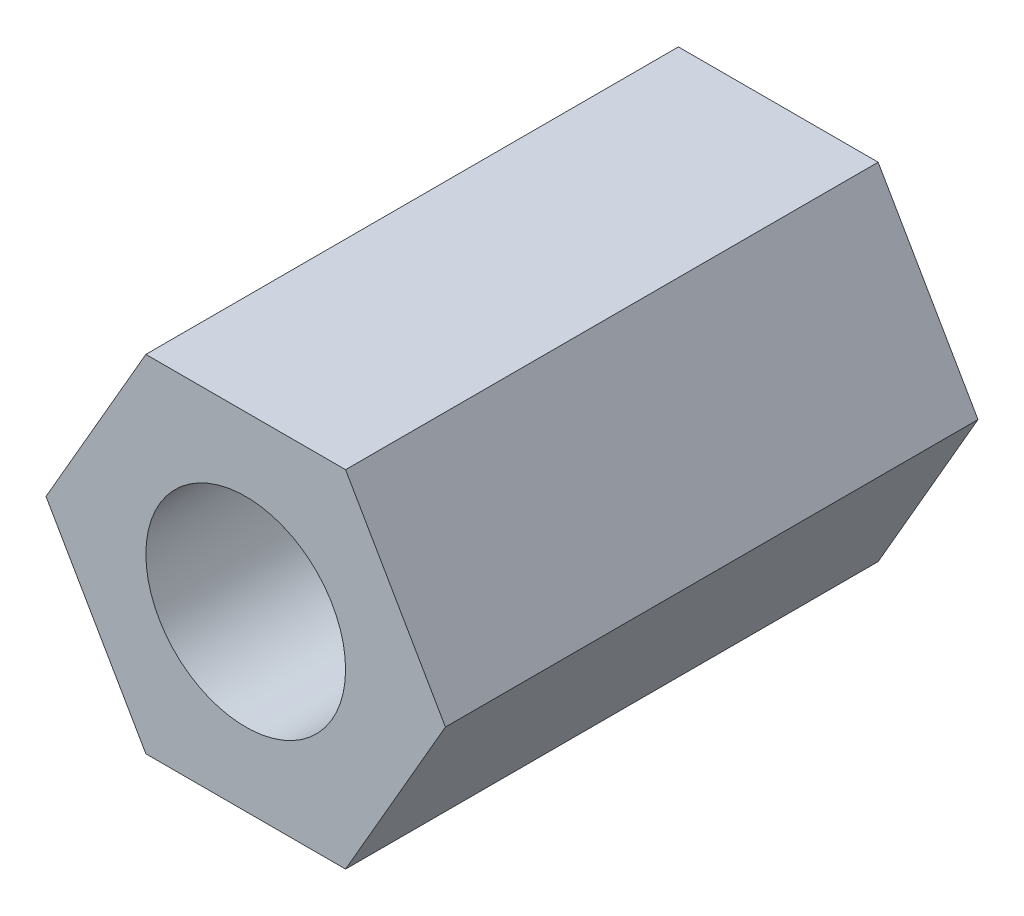
SolidWorks part; units mm, degrees
material "黄铜"
ref_plane "前视基准面" through (0, 0, 0) normal (0, 0, 1) x (1, 0, 0)
ref_plane "上视基准面" through (0, 0, 0) normal (0, 1, 0) x (1, 0, 0)
ref_plane "右视基准面" through (0, 0, 0) normal (1, 0, 0) x (0, 0, -1)
other "Configuration Table"
sketch "草图1" plane through (0, 0, 0) normal (0, 0, 1) x (1, 0, 0)
  line L1 (-1.5, 2.5981) -> (-3, 0)
  line L2 (-3, 0) -> (-1.5, -2.5981)
  line L3 (-1.5, -2.5981) -> (1.5, -2.5981)
  line L4 (1.5, -2.5981) -> (3, 0)
  line L5 (3, 0) -> (1.5, 2.5981)
  line L6 (1.5, 2.5981) -> (-1.5, 2.5981)
  circle A0 centre (0, 0) radius 2.5981 construction
  circle A1 centre (0, 0) radius 1.5
  dimension "D2" = 3
  dimension "D1" = 3
extrude "凸台-拉伸1" add sketch "草图1" along normal blind 8
